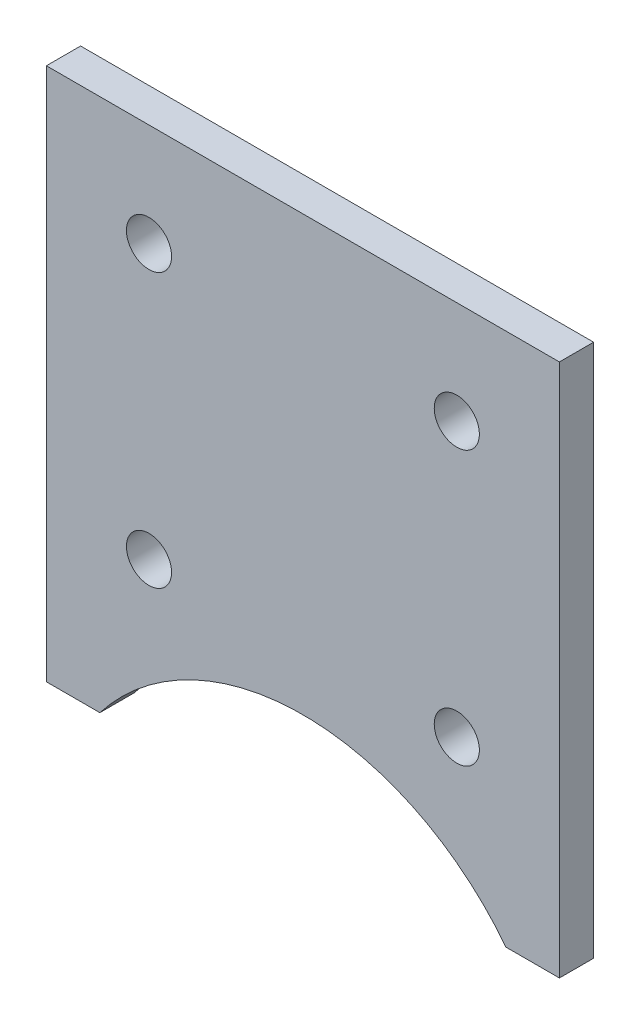
SolidWorks part; units mm, degrees
ref_plane "Front Plane" through (0, 0, 0) normal (0, 0, 1) x (1, 0, 0)
ref_plane "Top Plane" through (0, 0, 0) normal (0, 1, 0) x (1, 0, 0)
ref_plane "Right Plane" through (0, 0, 0) normal (1, 0, 0) x (0, 0, -1)
sketch "Sketch1" plane through (0, 0, 0) normal (0, 0, 1) x (1, 0, 0)
  line L0 (-37.5, 22.9169) -> (-37.5, 60.9169)
  line L1 (-37.5, 60.9169) -> (-22.5, 60.9169) construction
  line L2 (37.5, 60.9169) -> (37.5, 22.9169)
  line L3 (-37.5, 22.9169) -> (-29.6827, 22.9169)
  line L4 (-37.5, 60.9169) -> (-22.5, 60.9169) construction
  line L5 (-37.5, 60.9169) -> (-37.5, 45.9169)
  line L6 (-37.5, 45.9169) -> (-22.5, 45.9169) construction
  line L7 (-22.5, 60.9169) -> (-22.5, 45.9169) construction
  line L9 (37.5, 60.9169) -> (37.5, 45.9169) construction
  line L10 (37.5, 45.9169) -> (22.5, 45.9169) construction
  line L11 (22.5, 60.9169) -> (22.5, 45.9169) construction
  line L12 (29.6827, 22.9169) -> (37.5, 22.9169)
  line L13 (22.5, 60.9169) -> (37.5, 60.9169) construction
  line L15 (-37.5, 60.9169) -> (-37.5, 100.9169)
  line L16 (-37.5, 100.9169) -> (37.5, 100.9169)
  line L17 (37.5, 60.9169) -> (37.5, 100.9169)
  line L19 (-37.5, 0) -> (-37.5, 22.9169) construction
  line L20 (-37.5, 100.9169) -> (-22.5, 100.9169) construction
  line L21 (-37.5, 100.9169) -> (-37.5, 85.9169) construction
  line L22 (-37.5, 85.9169) -> (-22.5, 85.9169) construction
  line L23 (-22.5, 100.9169) -> (-22.5, 85.9169) construction
  line L24 (37.5, 100.9169) -> (22.5, 100.9169) construction
  line L25 (37.5, 100.9169) -> (37.5, 85.9169) construction
  line L26 (37.5, 85.9169) -> (22.5, 85.9169) construction
  line L27 (22.5, 100.9169) -> (22.5, 85.9169) construction
  line L28 (37.5, 0) -> (37.5, 22.9169) construction
  arc A0 (29.6827, 22.9169) -> (-29.6827, 22.9169) centre (0, 0) ccw
  circle A1 centre (0, 0) radius 37.5 construction
  dimension "D1" = 75
  dimension "D2" = 40
  dimension "D3" = 15
  dimension "D4" = 15
  dimension "D5" = 7.8173
  dimension "D6" = 38
  dimension "D7" = 15
extrude "Boss-Extrude1" add sketch "Sketch1" along normal blind 5 contours L15 L16 L17 L2 L12 A0 L3 L0
hole_wizard "M6 Clearance Hole1" positions "Sketch2" profile "Sketch3" hole size "M6" standard "ANSI Metric" end condition through all
sketch "Sketch2" plane through (0, 0, 0) normal (0, 0, -1) x (-1, 0, 0)
  point P0 (-22.5, 45.9169)
  point P3 (22.5, 45.9169)
  point P6 (22.5, 85.9169)
  point P9 (-22.5, 85.9169)
sketch "Sketch3" plane through (22.5, 45.9169, 0) normal (1, 0, 0) x (0, 1, 0)
  line L0 (0, 0) -> (0, 5)
  line L1 (0, 5) -> (3.3, 5)
  line L2 (3.3, 5) -> (3.3, 0.025)
  line L3 (3.3, 0.025) -> (3.325, 0)
  line L5 (3.325, 0) -> (0, 0)
  line L6 (-3.3, 0.025) -> (-3.325, 0) construction
  line L11 (0, -6.35) -> (0, 107.95) construction
  dimension "Thru Hole Dia." = 6.6
  dimension "Thru Hole Depth" = 5
  dimension "Near C'Sink Dia." = 6.65
  dimension "Near C'Sink Angle" = 90
